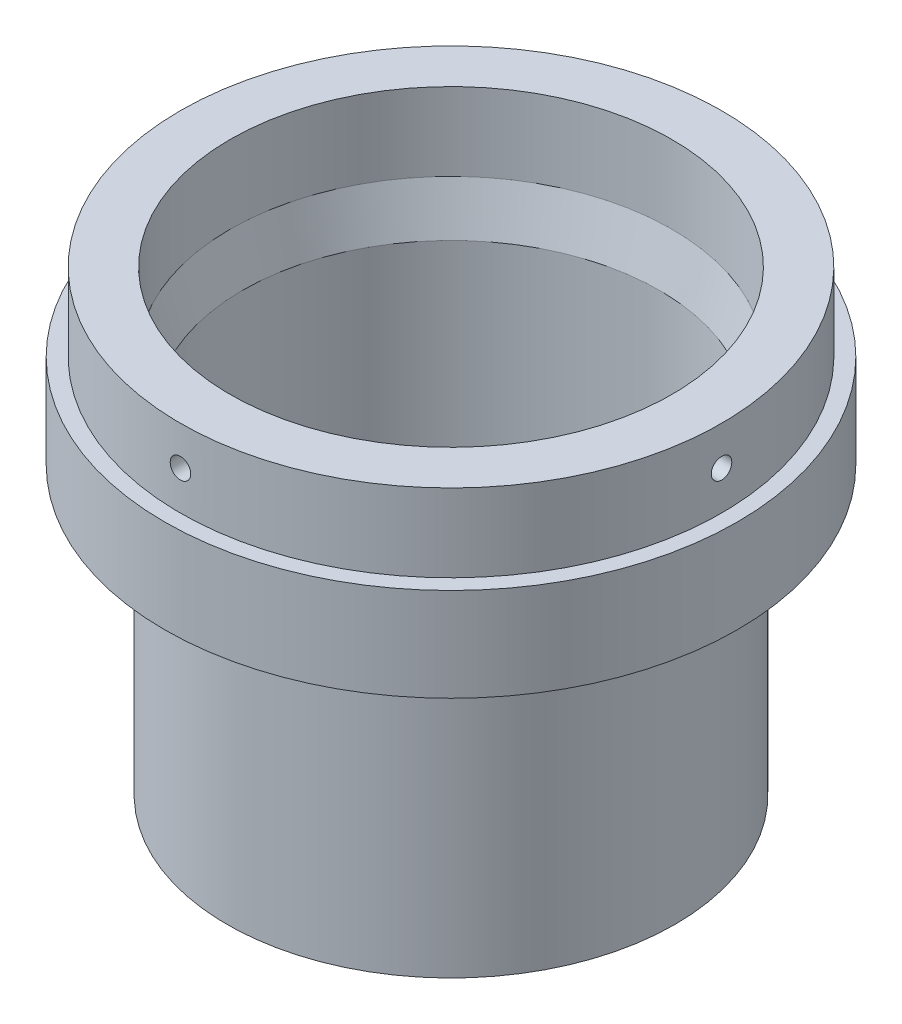
SolidWorks part; units mm, degrees
material "6061-T6 (SS)"
ref_plane "Front Plane" through (0, 0, 0) normal (0, 0, 1) x (1, 0, 0)
ref_plane "Top Plane" through (0, 0, 0) normal (0, 1, 0) x (1, 0, 0)
ref_plane "Right Plane" through (0, 0, 0) normal (1, 0, 0) x (0, 0, -1)
sketch "Sketch1" plane through (0, 0, 0) normal (0, 0, 1) x (1, 0, 0)
  line L0 (0, 0) -> (-71, 0) construction
  line L1 (-71, 0) -> (-71, 25)
  line L2 (-71, 25) -> (-87, 25)
  line L3 (-87, 25) -> (-87, 0)
  line L4 (-87, 0) -> (-92, 0)
  line L5 (-92, 0) -> (-92, -30)
  line L6 (-92, -30) -> (-72, -30)
  line L7 (-72, -30) -> (-72, -122)
  line L8 (-72, -122) -> (-67, -122)
  line L9 (-67, -122) -> (-67, -15)
  line L10 (-67, -15) -> (-71, 0)
  line L11 (-67, -122) -> (-17, -122) construction
  line L12 (-71, 25) -> (0, 25) construction
  line L13 (0, 25) -> (0, -50) construction
  dimension "D1" = 25
  dimension "D2" = 5
  dimension "D3" = 16
  dimension "D4" = 20
  dimension "D5" = 92
  dimension "D7" = 71
  dimension "D8" = 30
  dimension "D6" = 5
  dimension "D9" = 107
revolve "Revolve1" add sketch "Sketch1" angle 360 about L13
ref_plane "Plane1" through (-87, 0, 0) normal (-1, 0, 0) x (0, 0, 1)
sketch "Sketch2" plane through (-87, 0, 0) normal (-1, 0, 0) x (0, 0, 1)
  line L0 (-87, 12.5) -> (87, 12.5) construction
  line L1 (-87, 25) -> (-87, 0) construction
  line L2 (87, 0) -> (87, 25) construction
  line L3 (0, 0) -> (0, 25) construction
  line L4 (87, 25) -> (-87, 25) construction
  point P11 (0, 12.5)
hole_wizard "M6 Clearance Hole2" positions "Sketch5" profile "Sketch6" hole size "M6" standard "ISO"
sketch "Sketch5" plane through (-87, 0, 0) normal (-1, 0, 0) x (0, 0, 1)
  point P0 (0, 12.5)
sketch "Sketch6" plane through (-87, 12.5, 0) normal (0, 1, 0) x (0, 0, 1)
  line L0 (0, 0) -> (0, 14)
  line L1 (0, 14) -> (3.3, 12.0172)
  line L2 (3.3, 12.0172) -> (3.3, 0)
  line L5 (3.3, 0) -> (0, 0)
  line L10 (0, 14) -> (-3.3, 12.0172) construction
  line L11 (0, -6.35) -> (0, 107.95) construction
  dimension "Hole Dia." = 6.6
  dimension "Hole Depth" = 14
  dimension "Drill Angle" = 118
pattern_circular "CirPattern1" count 4 over 360 about axis through (0, 25, 0) along (0, 1, 0) of "M6 Clearance Hole2"
equation "\"nosecone_diameter\"= 184mm"
equation "\"nosecone_radius\"= \"nosecone_diameter\" / 2"
equation "\"nosecone_length\"= 700mm"
equation "\"nosecone_thickness\"= 5mm"
equation "\"shoulder_length\"= 25mm"
equation "\"shoulder_depth\"= 10mm"
equation "\"tip_length\"= 40mm"
equation "\"tip_shoulder_diameter\"= 12.64mm"
equation "\"D1@Sketch1\"=\"shoulder_length\""
equation "\"D2@Sketch1\"=\"nosecone_thickness\""
equation "\"D3@Sketch1\"=16mm"
equation "\"D4@Sketch1\"=20mm"
equation "\"D5@Sketch1\"=\"nosecone_diameter\"*0.5"
equation "\"D7@Sketch1\"=\"nosecone_radius\"-\"nosecone_thickness\"-16mm"
equation "\"D8@Sketch1\"=30mm"
equation "\"D6@Sketch1\"=5mm"
equation "\"D9@Sketch1\"=\"D5@Sketch1\"+0.5*\"D8@Sketch1\""
